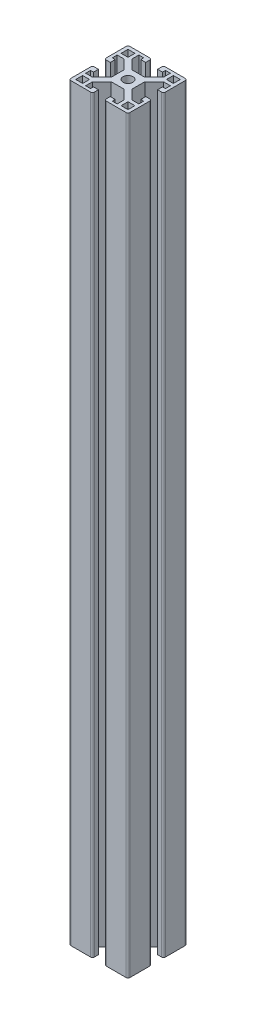
SolidWorks part; units mm, degrees
material "1060 Alloy"
ref_plane "Front Plane" through (0, 0, 0) normal (0, 0, 1) x (1, 0, 0)
ref_plane "Top Plane" through (0, 0, 0) normal (0, 1, 0) x (1, 0, 0)
ref_plane "Right Plane" through (0, 0, 0) normal (1, 0, 0) x (0, 0, -1)
sketch "Sketch1" plane through (0, 0, 0) normal (0, 1, 0) x (1, 0, 0)
  line L0 (-15, 7.5) -> (-15, -4.5)
  line L1 (-15, 7.5) -> (15, 7.5) construction
  line L2 (-15, 7.5) -> (-15, -7.5) construction
  line L3 (-15, -7.5) -> (15, -7.5) construction
  line L4 (15, 7.5) -> (15, -7.5) construction
  line L5 (0, -7.5) -> (0, 7.5) construction
  line L6 (-15, 0) -> (15, 0) construction
  line L7 (-15, 7.5) -> (-3, 7.5)
  line L8 (-15, -4.5) -> (-12, -4.5)
  line L9 (-12, -4.5) -> (-12, -2)
  line L10 (-12, -2) -> (-13.5, -2)
  line L11 (-13.5, -2) -> (-13.5, 0.5)
  line L12 (-13.5, 0.5) -> (-10, 0.5)
  line L13 (-5.25, -2.25) -> (5.25, -2.25) construction
  line L14 (-5.25, -2.25) -> (-5.25, -12.75) construction
  line L15 (-5.25, -12.75) -> (5.25, -12.75) construction
  line L16 (5.25, -2.25) -> (5.25, -12.75) construction
  line L17 (0, -12.75) -> (0, -2.25) construction
  line L18 (-5.25, -7.5) -> (5.25, -7.5) construction
  line L19 (-2.5857, -4.9143) -> (-15, 7.5) construction
  line L20 (-10, 0.5) -> (-5.25, -4.25)
  line L21 (-8, 2.5) -> (-3.25, -2.25)
  line L22 (-3, 7.5) -> (-3, 4.5)
  line L23 (-3, 4.5) -> (-5.5, 4.5)
  line L24 (-5.5, 4.5) -> (-5.5, 6)
  line L25 (-5.5, 6) -> (-8, 6)
  line L26 (-8, 6) -> (-8, 2.5)
  line L27 (5.5, 4.5) -> (5.5, 6)
  line L28 (-13.25, 5.75) -> (-9.75, 5.75)
  line L29 (-13.25, 5.75) -> (-13.25, 2.25)
  line L30 (-13.25, 2.25) -> (-9.75, 2.25)
  line L31 (-9.75, 5.75) -> (-9.75, 2.25)
  line L32 (-11.5, 2.25) -> (-11.5, 5.75) construction
  line L33 (-13.25, 4) -> (-9.75, 4) construction
  line L34 (13.25, 2.25) -> (9.75, 2.25)
  line L35 (13.25, 5.75) -> (13.25, 2.25)
  line L36 (13.25, 5.75) -> (9.75, 5.75)
  line L37 (9.75, 5.75) -> (9.75, 2.25)
  line L38 (3, 4.5) -> (5.5, 4.5)
  line L39 (3, 7.5) -> (3, 4.5)
  line L40 (5.5, 6) -> (8, 6)
  line L41 (8, 6) -> (8, 2.5)
  line L42 (15, 7.5) -> (3, 7.5)
  line L43 (13.5, 0.5) -> (10, 0.5)
  line L44 (13.5, -2) -> (13.5, 0.5)
  line L45 (12, -2) -> (13.5, -2)
  line L46 (15, 7.5) -> (15, -4.5)
  line L47 (15, -4.5) -> (12, -4.5)
  line L48 (12, -4.5) -> (12, -2)
  line L49 (8, 2.5) -> (3.25, -2.25)
  line L50 (10, 0.5) -> (5.25, -4.25)
  line L51 (-5.25, -4.25) -> (-5.25, -10.75)
  line L52 (-3.25, -2.25) -> (3.25, -2.25)
  line L53 (5.25, -4.25) -> (5.25, -10.75)
  line L54 (15, -22.5) -> (15, -10.5)
  line L55 (15, -10.5) -> (12, -10.5)
  line L56 (12, -10.5) -> (12, -13)
  line L57 (12, -13) -> (13.5, -13)
  line L58 (13.5, -13) -> (13.5, -15.5)
  line L59 (13.5, -15.5) -> (10, -15.5)
  line L60 (13.25, -17.25) -> (9.75, -17.25)
  line L61 (13.25, -20.75) -> (13.25, -17.25)
  line L62 (13.25, -20.75) -> (9.75, -20.75)
  line L63 (9.75, -20.75) -> (9.75, -17.25)
  line L64 (8, -21) -> (8, -17.5)
  line L65 (5.5, -21) -> (8, -21)
  line L66 (5.5, -19.5) -> (5.5, -21)
  line L67 (15, -22.5) -> (3, -22.5)
  line L68 (3, -22.5) -> (3, -19.5)
  line L69 (3, -19.5) -> (5.5, -19.5)
  line L70 (10, -15.5) -> (5.25, -10.75)
  line L71 (8, -17.5) -> (3.25, -12.75)
  line L72 (-3, -22.5) -> (-3, -19.5)
  line L73 (-3, -19.5) -> (-5.5, -19.5)
  line L74 (-5.5, -19.5) -> (-5.5, -21)
  line L75 (-5.5, -21) -> (-8, -21)
  line L76 (-8, -21) -> (-8, -17.5)
  line L77 (-15, -22.5) -> (-3, -22.5)
  line L78 (-9.75, -20.75) -> (-9.75, -17.25)
  line L79 (-13.25, -20.75) -> (-9.75, -20.75)
  line L80 (-13.25, -20.75) -> (-13.25, -17.25)
  line L81 (-13.25, -17.25) -> (-9.75, -17.25)
  line L82 (-13.5, -15.5) -> (-10, -15.5)
  line L83 (-13.5, -13) -> (-13.5, -15.5)
  line L84 (-12, -13) -> (-13.5, -13)
  line L85 (-15, -22.5) -> (-15, -10.5)
  line L86 (-15, -10.5) -> (-12, -10.5)
  line L87 (-12, -10.5) -> (-12, -13)
  line L88 (-3.25, -12.75) -> (3.25, -12.75)
  line L89 (-8, -17.5) -> (-3.25, -12.75)
  line L90 (-10, -15.5) -> (-5.25, -10.75)
  circle A0 centre (0, -7.5) radius 2.5
  point P0 (0, 0)
  point P18 (-11.5, 4)
  dimension "D7" = 1.5
  dimension "D19" = 5
  dimension "D1" = 30
  dimension "D2" = 15
  dimension "D3" = 12
  dimension "D4" = 12
  dimension "D5" = 3
  dimension "D6" = 2.5
  dimension "D8" = 2.5
  dimension "D9" = 10.5
  dimension "D10" = 3.5
  dimension "D11" = 45
  dimension "D12" = 3
  dimension "D13" = 2.5
  dimension "D14" = 1.5
  dimension "D15" = 2.5
  dimension "D16" = 3.5
  dimension "D17" = 3.5
  dimension "D18" = 3.5
extrude "Boss-Extrude1" add sketch "Sketch1" against normal blind 380
fillet "Fillet1" radius 1 12 edges at (-3, -190, -7.5) (-15, -190, -7.5) (-15, -190, 4.5) (3, -190, -7.5) (15, -190, -7.5) (15, -190, 4.5) (15, -190, 10.5) (3, -190, 22.5) (15, -190, 22.5) (-3, -190, 22.5) (-15, -190, 22.5) (-15, -190, 10.5)
